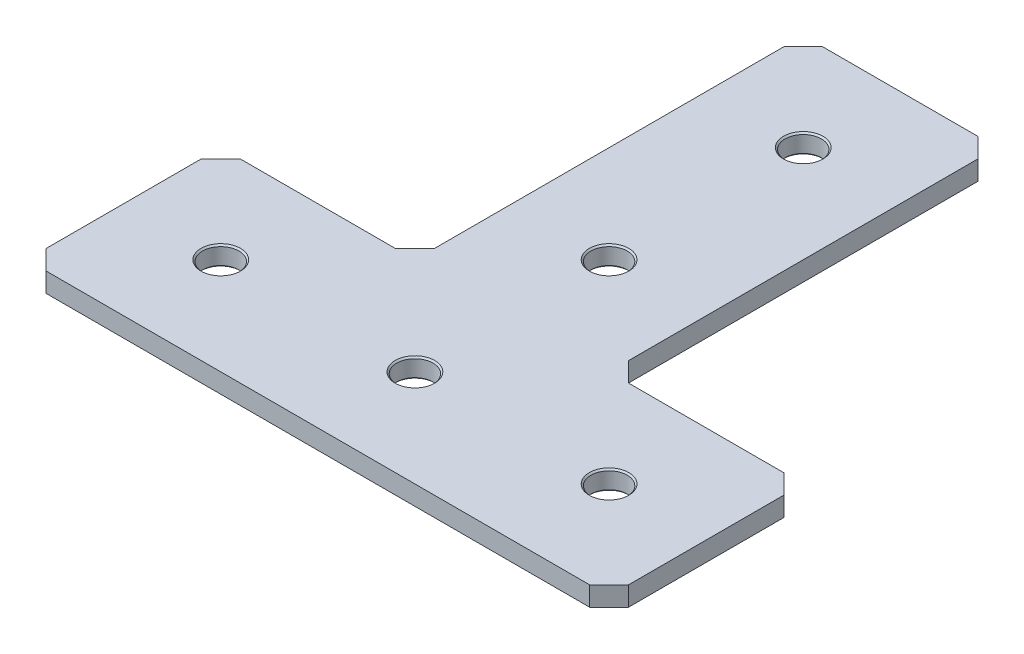
SolidWorks part; units mm, degrees
ref_plane "Front Plane" through (0, 0, 0) normal (0, 0, 1) x (1, 0, 0)
ref_plane "Top Plane" through (0, 0, 0) normal (0, 1, 0) x (1, 0, 0)
ref_plane "Right Plane" through (0, 0, 0) normal (1, 0, 0) x (0, 0, -1)
sketch "Sketch1" plane through (0, 0, 0) normal (0, 1, 0) x (1, 0, 0)
  line L1 (0, 0) -> (-25.4, 0)
  line L2 (0, 0) -> (0, 50.8)
  line L3 (0, 50.8) -> (25.4, 50.8)
  line L4 (25.4, 0) -> (25.4, 50.8)
  line L6 (50.8, -25.4) -> (-25.4, -25.4)
  line L7 (50.8, -25.4) -> (50.8, 0)
  line L8 (50.8, 0) -> (25.4, 0)
  line L9 (-25.4, -25.4) -> (-25.4, 0)
  point P11 (12.7, 0)
  dimension "D1" = 25.4
  dimension "D2" = 50.8
  dimension "D3" = 25.4
  dimension "D4" = 76.2
extrude "Boss-Extrude1" add sketch "Sketch1" along normal blind 2.54
hole_wizard "3/16 (0.1875) Diameter Hole1" positions "Sketch3" profile "Sketch2" hole size "3/16" standard "ANSI Inch" end condition through all
sketch "Sketch3" plane through (0, 2.54, 0) normal (0, 1, 0) x (1, 0, 0)
  line L0 (12.7, 50.8) -> (12.7, -25.4) construction
  line L1 (25.4, 50.8) -> (0, 50.8) construction
  line L2 (-25.4, -25.4) -> (50.8, -25.4) construction
  line L3 (50.8, -12.7) -> (-25.4, -12.7) construction
  line L4 (50.8, -25.4) -> (50.8, 0) construction
  line L5 (-25.4, 0) -> (-25.4, -25.4) construction
  point P14 (12.7, 38.1)
  point P16 (12.7, 12.7)
  point P18 (12.7, -12.7)
  point P20 (38.1, -12.7)
  point P22 (-12.7, -12.7)
  dimension "D1" = 12.7
  dimension "D2" = 38.1
  dimension "D3" = 12.7
  dimension "D4" = 12.7
sketch "Sketch2" plane through (12.7, 2.54, -38.1) normal (1, 0, 0) x (0, 0, 1)
  line L0 (0, 0) -> (0, 2.54)
  line L1 (0, 2.54) -> (2.3812, 2.54)
  line L2 (2.3812, 2.54) -> (2.3812, 0)
  line L5 (2.3812, 0) -> (0, 0)
  line L11 (0, -6.35) -> (0, 107.95) construction
  dimension "Thru Hole Dia." = 4.7625
  dimension "Thru Hole Depth" = 2.54
chamfer "Chamfer1" distance 2.54 angle 45 8 edges at (-25.4, 1.27, 25.4) (50.8, 1.27, 25.4) (50.8, 1.27, 0) (25.4, 1.27, 0) (25.4, 1.27, -50.8) (0, 1.27, -50.8) (-25.4, 1.27, 0) (0, 1.27, 0)
chamfer "Chamfer2" distance 0.2 angle 45 10 edges at (-12.7, 2.54, 15.0812) (-12.7, 0, 15.0812) (38.1, 2.54, 15.0812) (38.1, 0, 15.0812) (12.7, 2.54, 15.0812) (12.7, 0, 15.0812) (12.7, 2.54, -10.3187) (12.7, 0, -10.3187) (12.7, 2.54, -35.7187) (12.7, 0, -35.7187)
